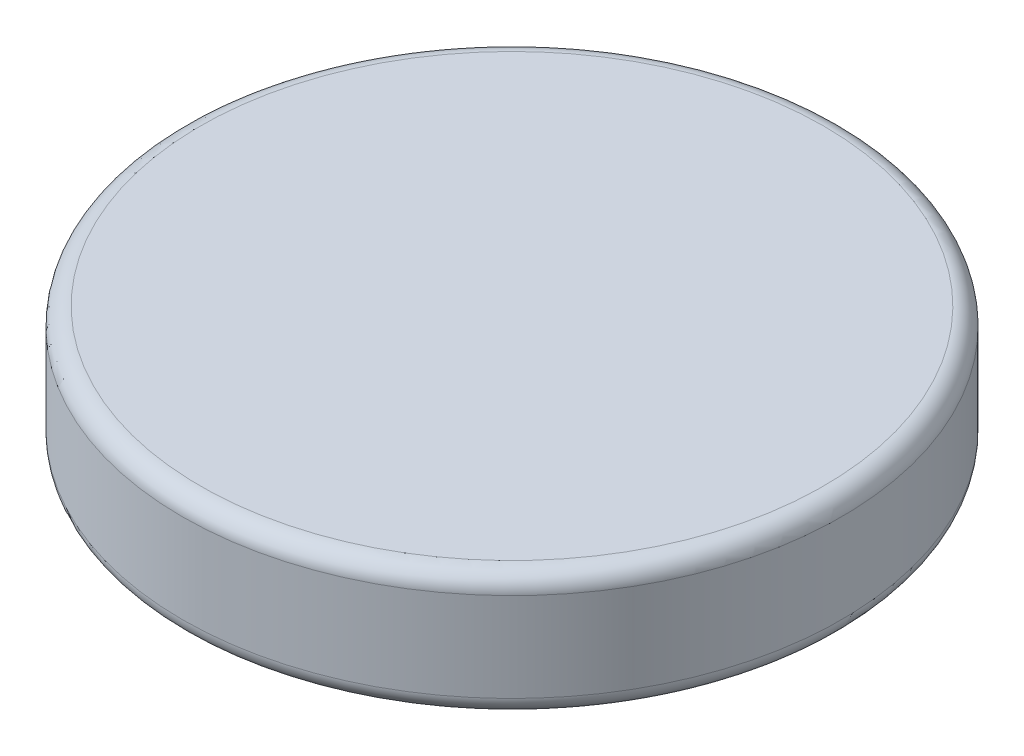
SolidWorks part; units mm, degrees
ref_plane "Front Plane" through (0, 0, 0) normal (0, 0, 1) x (1, 0, 0)
ref_plane "Top Plane" through (0, 0, 0) normal (0, 1, 0) x (1, 0, 0)
ref_plane "Right Plane" through (0, 0, 0) normal (1, 0, 0) x (0, 0, -1)
sketch "Sketch2" plane through (0, 0, 0) normal (0, 0, 1) x (1, 0, 0)
  line L0 (0, 0) -> (0, 3) construction
  line L1 (0, 3) -> (-11, 3) construction
  line L2 (-11, 3) -> (-11, 13) construction
  line L3 (-11, 13) -> (29, 13) construction
  line L4 (29, 13) -> (29, 3) construction
  line L5 (29, 3) -> (18, 3) construction
  line L6 (18, 3) -> (18, 0) construction
  line L7 (18, 0) -> (0, 0) construction
  line L11 (1.5, 1.5) -> (1.5, 3.5)
  line L12 (0.5, 4.5) -> (-9.5, 4.5)
  line L16 (-9.5, 4.5) -> (-9.5, 11.5)
  line L17 (-9.5, 11.5) -> (9, 11.5)
  line L21 (9, 1.5) -> (1.5, 1.5)
  line L22 (9, 1.5) -> (9, 11.5)
  line L23 (1.5, 1.5) -> (1.5, 4.5) construction
  line L24 (1.5, 4.5) -> (-9.5, 4.5) construction
  line L26 (-9.5, 11.5) -> (27.5, 11.5) construction
  line L27 (27.5, 4.5) -> (16.5, 4.5) construction
  line L28 (27.5, 11.5) -> (27.5, 4.5) construction
  line L29 (16.5, 4.5) -> (16.5, 1.5) construction
  line L30 (16.5, 1.5) -> (1.5, 1.5) construction
  arc A1 (1.5, 3.5) -> (0.5, 4.5) centre (0.5, 3.5) ccw
  point P23 (9, 11.5)
  point P24 (9, 1.5)
  dimension "D7" = 18.5
  dimension "D6" = 1
  dimension "D1" = 40
  dimension "D2" = 18
  dimension "D3" = 10
  dimension "D4" = 3
  dimension "D5" = 1.5
revolve "Revolve1" add sketch "Sketch2" angle 360 about L22
sketch "Sketch3" plane through (0, 1.5, 0) normal (0, -1, 0) x (1, 0, 0)
  circle A0 centre (9, 0) radius 4.1416
  circle A1 centre (9, 0) radius 7.5
  circle A2 centre (9, 0) radius 7.5 construction
  dimension "D1" = 0
extrude "Cut-Extrude1" cut sketch "Sketch3" against normal blind 7
fillet "Fillet2" radius 1 2 edges at (9, 11.5, -18.5) (9, 4.5, -18.5)
fillet "Fillet3" radius 1 1 edges at (9, 1.5, -7.5)
